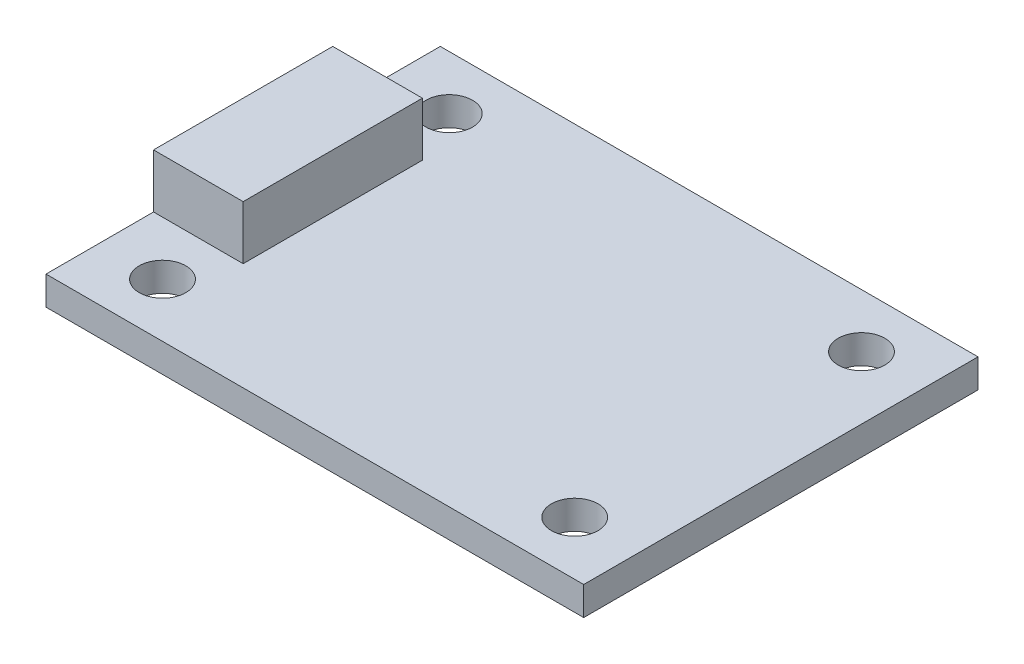
SolidWorks part; units mm, degrees
ref_plane "前视基准面" through (0, 0, 0) normal (0, 0, 1) x (1, 0, 0)
ref_plane "上视基准面" through (0, 0, 0) normal (0, 1, 0) x (1, 0, 0)
ref_plane "右视基准面" through (0, 0, 0) normal (1, 0, 0) x (0, 0, -1)
other "Configuration Table"
sketch "草图1" plane through (0, 0, 0) normal (0, 1, 0) x (1, 0, 0)
  line L0 (0, 11) -> (30, 11) construction
  line L1 (0, 0) -> (30, 0)
  line L2 (0, 0) -> (0, 22)
  line L3 (0, 22) -> (30, 22)
  line L4 (30, 0) -> (30, 22)
  line L5 (15, 22) -> (15, 0) construction
  circle A0 centre (3.5, 3) radius 1.3
  circle A1 centre (26.5, 3) radius 1.3
  circle A2 centre (26.5, 19) radius 1.3
  circle A3 centre (3.5, 19) radius 1.3
  dimension "D3" = 2.6
  dimension "D4" = 23
  dimension "D1" = 30
  dimension "D2" = 22
  dimension "D5" = 8
extrude "凸台-拉伸1" add sketch "草图1" along normal blind 1.6
sketch "草图2" plane through (0, 1.6, 0) normal (0, 1, 0) x (1, 0, 0)
  line L0 (0, 22) -> (0, 0) construction
  line L1 (0, 16) -> (5, 16)
  line L2 (0, 16) -> (0, 6)
  line L3 (0, 6) -> (5, 6)
  line L4 (5, 16) -> (5, 6)
  line L5 (30, 11) -> (5, 11) construction
  line L6 (30, 0) -> (30, 22) construction
  dimension "D1" = 10
  dimension "D2" = 5
extrude "凸台-拉伸2" add sketch "草图2" along normal blind 3
